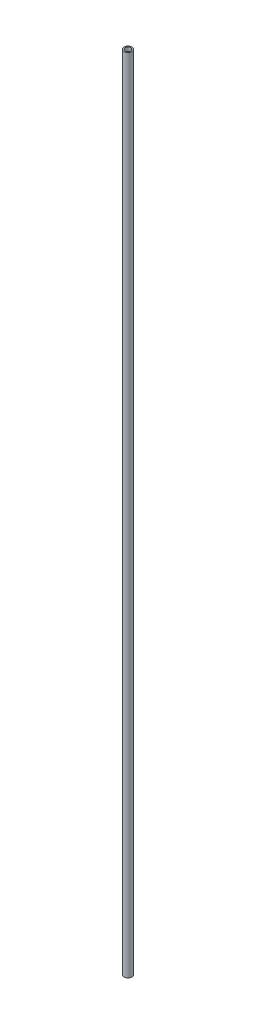
SolidWorks part; units mm, degrees
material "Silicon"
ref_plane "Front Plane" through (0, 0, 0) normal (0, 0, 1) x (1, 0, 0)
ref_plane "Top Plane" through (0, 0, 0) normal (0, 1, 0) x (1, 0, 0)
ref_plane "Right Plane" through (0, 0, 0) normal (1, 0, 0) x (0, 0, -1)
sketch "Sketch1" plane through (0, 0, 0) normal (0, 1, 0) x (1, 0, 0)
  circle A0 centre (0, 0) radius 3.5
  circle A1 centre (0, 0) radius 2.5
extrude "Boss-Extrude1" add sketch "Sketch1" along normal blind 700
